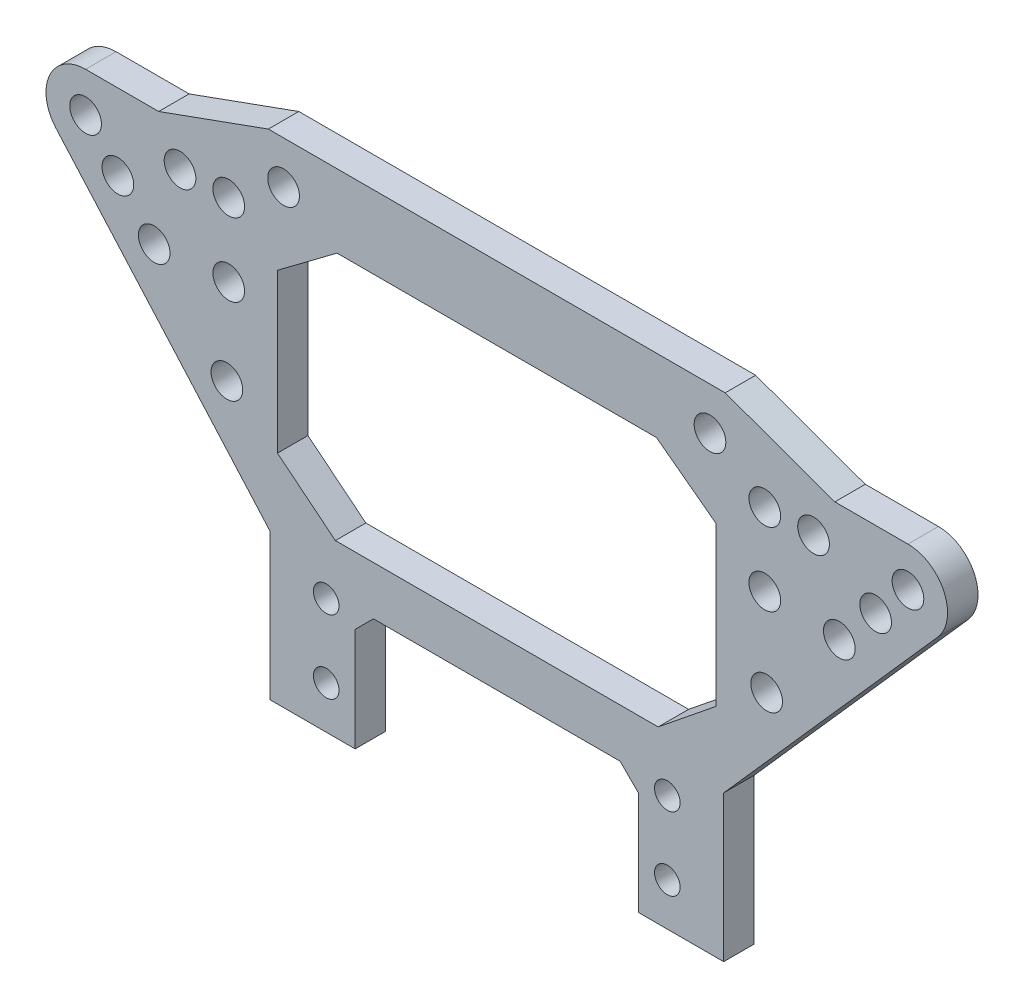
SolidWorks part; units mm, degrees
material "7050-T73510"
ref_plane "前视基准面" through (0, 0, 0) normal (0, 0, 1) x (1, 0, 0)
ref_plane "上视基准面" through (0, 0, 0) normal (0, 1, 0) x (1, 0, 0)
ref_plane "右视基准面" through (0, 0, 0) normal (1, 0, 0) x (0, 0, -1)
sketch "草图2" plane through (0, 0, 0) normal (0, 0, 1) x (1, 0, 0)
  line L0 (-23.25, 0) -> (23.25, 0)
  line L1 (23.25, 0) -> (23.25, -16)
  line L2 (-23.25, 0) -> (-23.25, -16)
  line L3 (23.25, -16) -> (37.25, -16)
  line L4 (37.25, -16) -> (37.25, 8)
  line L5 (37.25, 8) -> (72.3682, 47.6929)
  line L6 (0, 0) -> (0, 65) construction
  line L7 (67.5, 58.5) -> (55.5, 58.5)
  line L8 (55.5, 58.5) -> (37.5, 65)
  line L9 (37.5, 65) -> (-37.5, 65)
  line L10 (-55.5, 58.5) -> (-37.5, 65)
  line L11 (-67.5, 58.5) -> (-55.5, 58.5)
  line L12 (-37.25, 8) -> (-72.3682, 47.6929)
  line L13 (-37.25, -16) -> (-37.25, 8)
  line L14 (-23.25, -16) -> (-37.25, -16)
  line L15 (-23.25, 0) -> (-23.25, -16)
  line L16 (67.5, 52) -> (56.2353, 39.2679)
  arc A0 (72.3682, 47.6929) -> (67.5, 58.5) centre (67.5, 52) ccw
  arc A1 (-72.3682, 47.6929) -> (-67.5, 58.5) centre (-67.5, 52) cw
  circle A2 centre (28, -9) radius 2.1
  circle A3 centre (28, 3) radius 2.1
  circle A4 centre (44.308, 25.7868) radius 2.6
  circle A5 centre (56.2353, 39.2679) radius 2.6
  circle A6 centre (62.199, 46.0084) radius 2.6
  circle A7 centre (67.5, 52) radius 2.6
  circle A8 centre (44, 40) radius 2.6
  circle A9 centre (44, 52) radius 2.6
  circle A10 centre (52, 52) radius 2.6
  circle A11 centre (35, 58) radius 2.6
  circle A12 centre (-67.5, 52) radius 2.6
  circle A13 centre (-62.199, 46.0084) radius 2.6
  circle A14 centre (-56.2353, 39.2679) radius 2.6
  circle A15 centre (-44.308, 25.7868) radius 2.6
  circle A16 centre (-44, 40) radius 2.6
  circle A17 centre (-52, 52) radius 2.6
  circle A18 centre (-44, 52) radius 2.6
  circle A19 centre (-35, 58) radius 2.6
  circle A20 centre (-28, -9) radius 2.1
  circle A21 centre (-28, 3) radius 2.1
  point P4 (0, 0)
  dimension "D3" = 13
  dimension "D7" = 52
  dimension "D11" = 12
  dimension "D13" = 28
  dimension "D14" = 4.2
  dimension "D16" = 7
  dimension "D18" = 8
  dimension "D19" = 8
  dimension "D20" = 9
  dimension "D21" = 18
  dimension "D22" = 44
  dimension "D23" = 5.2
  dimension "D24" = 12
  dimension "D25" = 5.2
  dimension "D1" = 46.5
  dimension "D2" = 16
  dimension "D4" = 14
  dimension "D5" = 24
  dimension "D6" = 67.5
  dimension "D8" = 65
  dimension "D9" = 37.5
  dimension "D10" = 12
  dimension "D12" = 7
  dimension "D15" = 35
  dimension "D17" = 13
extrude "凸台-拉伸1" add sketch "草图2" along normal blind 5
sketch "草图3" plane through (0, 0, 5) normal (0, 0, 1) x (1, 0, 0)
  line L0 (0, 0) -> (0, 79.0978) construction
  line L1 (-23.25, 0) -> (23.25, 0) construction
  line L2 (-26.2193, 53) -> (26.2193, 53)
  line L3 (26.2193, 53) -> (36, 45.6758)
  line L4 (36, 45.6758) -> (36, 19.6758)
  line L5 (36, 19.6758) -> (26.4927, 12)
  line L6 (26.4927, 12) -> (-26.4927, 12)
  line L7 (37.5, 65) -> (-37.5, 65) construction
  line L8 (-36, 19.6758) -> (-26.4927, 12)
  line L9 (-36, 45.6758) -> (-36, 19.6758)
  line L10 (-26.2193, 53) -> (-36, 45.6758)
  point P13 (0, 12)
  point P16 (0, 53)
  dimension "D1" = 12
  dimension "D2" = 12
  dimension "D3" = 36
  dimension "D4" = 26
extrude "切除-拉伸1" cut sketch "草图3" against normal blind 5
sketch "草图5" plane through (0, 0, 5) normal (0, 0, 1) x (1, 0, 0)
  line L0 (-23.25, 0) -> (-23.25, 4)
  line L1 (-23.25, 4) -> (23.25, 4)
  line L2 (23.25, 4) -> (23.25, 0)
  line L3 (23.25, 0) -> (-23.25, 0)
  dimension "D1" = 4
extrude "切除-拉伸2" cut sketch "草图5" against normal blind 5
chamfer "倒角2" distance 3 angle 45 2 edges at (23.25, 4, 2.5) (-23.25, 4, 2.5)
